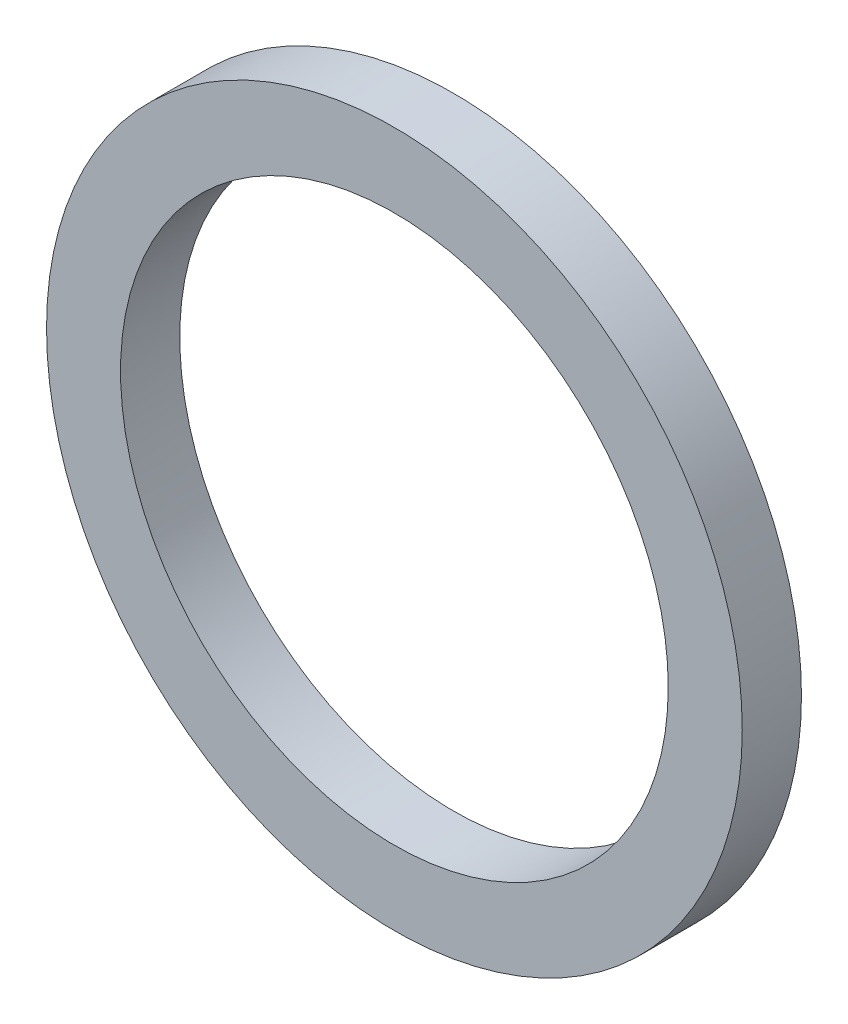
SolidWorks part; units mm, degrees
ref_plane "Front Plane" through (0, 0, 0) normal (0, 0, 1) x (1, 0, 0)
ref_plane "Top Plane" through (0, 0, 0) normal (0, 1, 0) x (1, 0, 0)
ref_plane "Right Plane" through (0, 0, 0) normal (1, 0, 0) x (0, 0, -1)
sketch "Sketch1" plane through (0, 0, 0) normal (0, 0, 1) x (1, 0, 0)
  circle A0 centre (0, 0) radius 23.5
  circle A1 centre (0, 0) radius 18.5
  dimension "D1" = 47
  dimension "D2" = 37
extrude "Boss-Extrude1" add sketch "Sketch1" along normal blind 4
